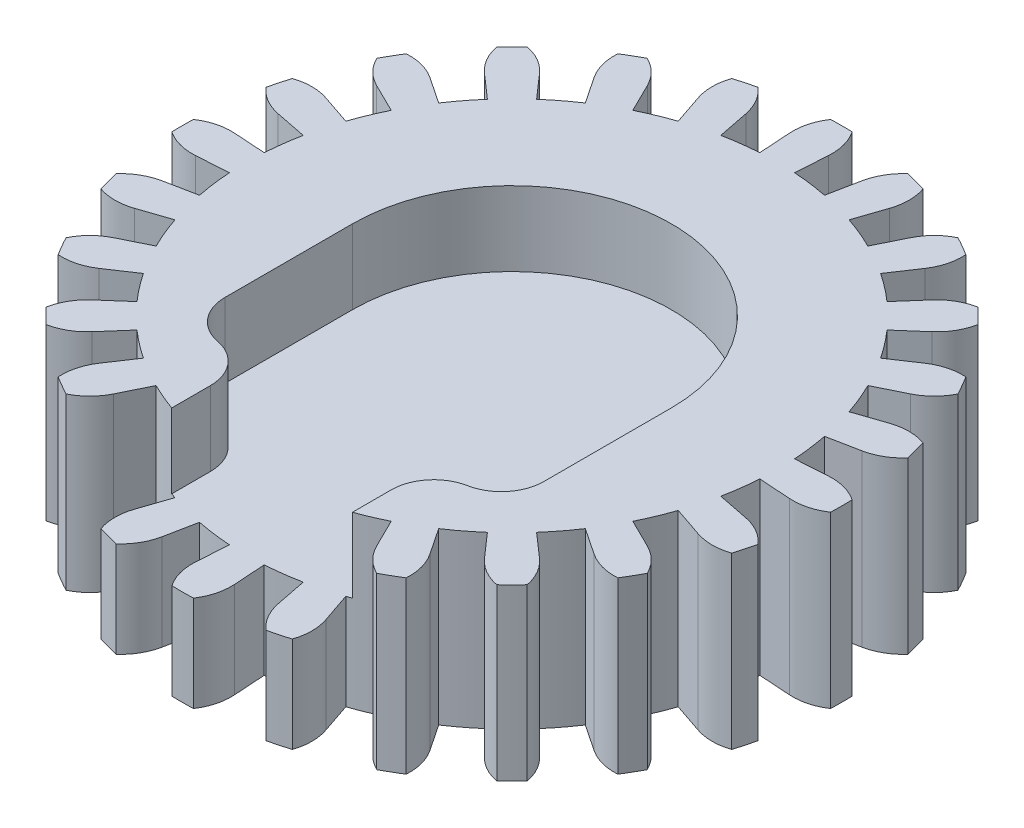
SolidWorks part; units mm, degrees
ref_plane "Front Plane" through (0, 0, 0) normal (0, 0, 1) x (1, 0, 0)
ref_plane "Top Plane" through (0, 0, 0) normal (0, 1, 0) x (1, 0, 0)
ref_plane "Right Plane" through (0, 0, 0) normal (1, 0, 0) x (0, 0, -1)
sketch "Sketch10" plane through (0, 0, 0) normal (0, 1, 0) x (1, 0, 0)
  line L0 (0, 0) -> (28.3448, 0) construction
  line L1 (0, 0) -> (12.3931, 1.6316) construction
  line L2 (0, 0) -> (21.5394, 1.4118) construction
  line L3 (0, 0) -> (24.4578, 0.8007) construction
  line L4 (13.97, 0.9156) -> (12.4732, 0.8175)
  line L5 (0, 0) -> (12.3931, 1.6316)
  line L9 (0, 0) -> (12.3931, -1.6316)
  line L13 (12.4732, -0.8175) -> (13.97, -0.9156)
  circle A0 centre (0, 0) radius 12.5 construction
  circle A1 centre (0, 0) radius 14 construction
  circle A2 centre (0, 0) radius 15.5 construction
  arc A3 (13.97, 0.9156) -> (15.4917, 0.5071) centre (14.1301, -1.5265) cw
  arc A4 (12.3931, 1.6316) -> (12.4732, 0.8175) centre (0, 0) cw
  arc A5 (13.97, -0.9156) -> (15.4917, -0.5071) centre (14.1301, 1.5265) ccw
  arc A6 (12.3931, -1.6316) -> (12.4732, -0.8175) centre (0, 0) ccw
  arc A7 (15.4917, 0.5071) -> (15.4917, -0.5071) centre (0, 0) cw
  dimension "D1" = 25
  dimension "D2" = 28
  dimension "D3" = 31
  dimension "D4" = 7.5
  dimension "D5" = 3.75
  dimension "D6" = 1.875
  dimension "D7" = 0
  dimension "D8" = 0
extrude "Boss-Extrude3" add sketch "Sketch10" along normal blind 8 contours A7 A3 L4 A4 L5 L9 A6 L13 A5
pattern_circular "CirPattern1" count 24 every 15 about axis through (0, 0, 0) along (0, 1, 0) of "Boss-Extrude3"
sketch "Sketch11" plane through (0, 8, 0) normal (0, 1, 0) x (1, 0, 0)
  line L0 (-7.5, 0) -> (-7.5, -8)
  line L1 (-7.5, -8) -> (-4.25, -8)
  line L2 (-4.25, -8) -> (-4.25, -23)
  line L3 (-4.25, -23) -> (4.25, -23)
  line L4 (4.25, -23) -> (4.25, -8)
  line L5 (4.25, -8) -> (7.5, -8)
  line L6 (7.5, -8) -> (7.5, 0)
  circle A0 centre (0, 0) radius 7.5 construction
  arc A1 (-7.5, 0) -> (7.5, 0) centre (0, 0) cw
  dimension "D1" = 15
  dimension "D2" = 3.25
  dimension "D3" = 3.25
  dimension "D4" = 8
  dimension "D5" = 8
  dimension "D6" = 15
extrude "Cut-Extrude1" cut sketch "Sketch11" against normal blind 3.5
fillet "Fillet3" radius 2 2 edges at (7.5, 6.25, 8) (-7.5, 6.25, 8)
fillet "Fillet4" radius 2 2 edges at (4.25, 6.25, 8) (-4.25, 6.25, 8)
sketch "Sketch12" plane through (0, 8, 0) normal (0, 1, 0) x (1, 0, 0)
  line L0 (-4.25, -11.7553) -> (4.25, -11.7553)
  line L1 (4.25, -11.7553) -> (5.7048, -11.7553)
  line L2 (5.7048, -11.7553) -> (5.7048, -15.7553)
  line L3 (5.7048, -15.7553) -> (-5.2952, -15.7553)
  line L4 (-5.2952, -15.7553) -> (-5.2952, -11.7553)
  line L5 (-5.2952, -11.7553) -> (-4.25, -11.7553)
  dimension "D1" = 11
  dimension "D2" = 4
extrude "Cut-Extrude2" cut sketch "Sketch12" against normal blind 3.5
